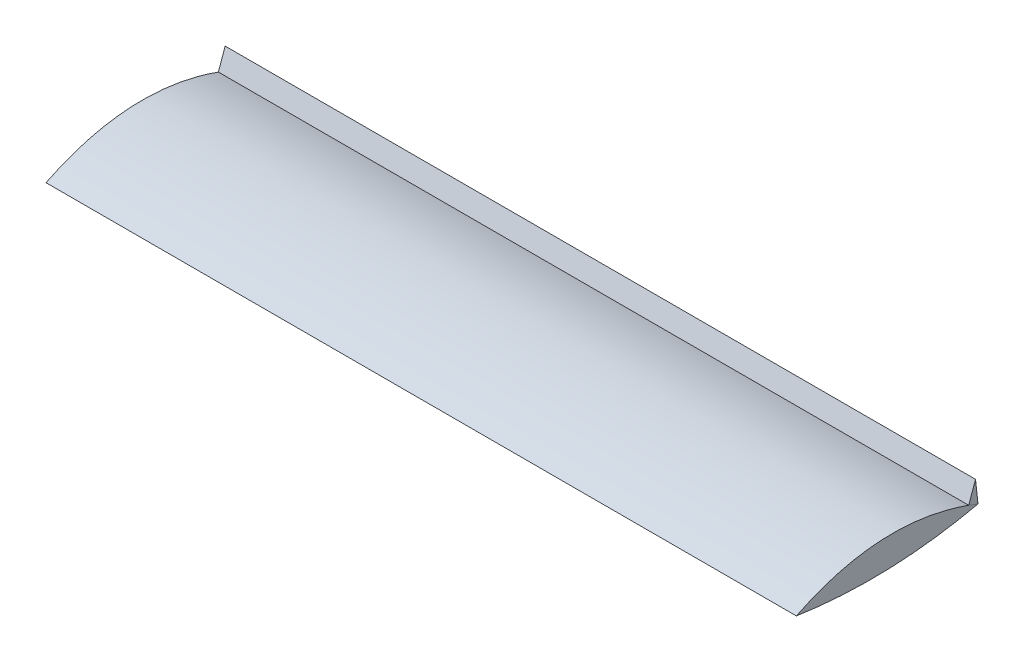
SolidWorks part; units mm, degrees
ref_plane "Front Plane" through (0, 0, 0) normal (0, 0, 1) x (1, 0, 0)
ref_plane "Top Plane" through (0, 0, 0) normal (0, 1, 0) x (1, 0, 0)
ref_plane "Right Plane" through (0, 0, 0) normal (1, 0, 0) x (0, 0, -1)
sketch "Sketch2" plane through (0, 0, 0) normal (1, 0, 0) x (0, 0, -1)
  line L0 (132.7666, -12.751) -> (129.4337, 17.8358)
  line L1 (129.4337, 17.8358) -> (120.2097, -8.0068)
  line L2 (120.2097, -8.0068) -> (132.7666, -12.751)
  spline S0 degree 2 poles (-113.1792, -21.0676) (5.9456, 37.8044) (132.7666, -12.751) knots 0 0 0 1 1 1
  spline S1 degree 2 poles (132.7666, -12.751) (11.2925, -39.9702) (-113.1792, -21.0676) knots 0 0 0 1 1 1
  point P0 (-113.1792, -21.0676)
  point P1 (132.7666, -12.751)
  dimension "D1" = 254
extrude "Boss-Extrude1" add sketch "Sketch2" along normal blind 1016
